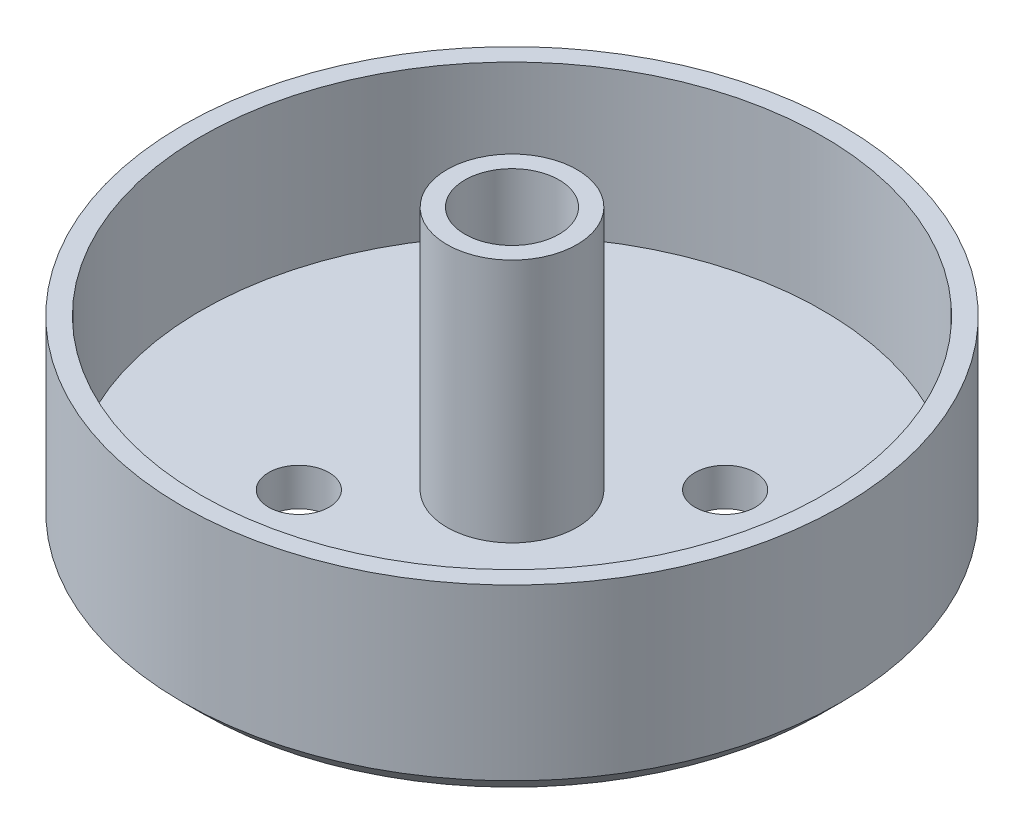
SolidWorks part; units mm, degrees
material "Stainless Steel (ferritic)"
ref_plane "Front Plane" through (0, 0, 0) normal (0, 0, 1) x (1, 0, 0)
ref_plane "Top Plane" through (0, 0, 0) normal (0, 1, 0) x (1, 0, 0)
ref_plane "Right Plane" through (0, 0, 0) normal (1, 0, 0) x (0, 0, -1)
sketch "Sketch1" plane through (0, 0, 0) normal (0, 1, 0) x (1, 0, 0)
  circle A0 centre (0, 0) radius 17.5
  circle A1 centre (0, 0) radius 2.5
  dimension "D1" = 35
  dimension "D2" = 5
extrude "Body" add sketch "Sketch1" along normal blind 2
sketch "Sketch4" plane through (0, 2, 0) normal (0, 1, 0) x (1, 0, 0)
  circle A0 centre (0, 0) radius 2.5
  circle A1 centre (0, 0) radius 3.45
  circle A2 centre (0, 0) radius 2.5 construction
  dimension "D1" = 6.9
extrude "Shaft" add sketch "Sketch4" along normal offset from surface (13 mm away) 15 up to face at (0, 0, 17.5)
sketch "Sketch5" plane through (0, 2, 0) normal (0, 1, 0) x (1, 0, 0)
  circle A0 centre (0, 0) radius 16.5
  circle A1 centre (0, 0) radius 17.5
  circle A2 centre (0, 0) radius 17.5 construction
  dimension "D1" = 1
extrude "Border" add sketch "Sketch5" along normal offset from surface (8 mm away) 10 up to face at (0, 0, 17.5)
sketch "Sketch3" plane through (0, 0, 0) normal (0, -1, 0) x (-1, 0, 0)
  line L0 (5.6569, 5.6569) -> (-5.6569, -5.6569) construction
  line L9 (5.6569, -5.6569) -> (-5.6569, 5.6569) construction
  line L10 (-8.25, 0) -> (8.25, 0) construction
  circle A1 centre (5.6569, 5.6569) radius 1.6
  circle A2 centre (5.6569, -5.6569) radius 1.6
  circle A3 centre (-5.6569, -5.6569) radius 1.6
  circle A4 centre (-5.6569, 5.6569) radius 1.6
  point P0 (0, 0)
  point P3 (0, 0)
  dimension "D2" = 3.2
  dimension "D1" = 16
  dimension "D3" = 45
extrude "Screw holes" cut sketch "Sketch3" against normal blind 3
chamfer "Screw chamfer" distance 1 1 edges at (0, 0, 17.5)
equation "\"HOLE_DIAMETER\"= 3.2mm"
equation "\"D2@Sketch3\"=\"HOLE_DIAMETER\""
